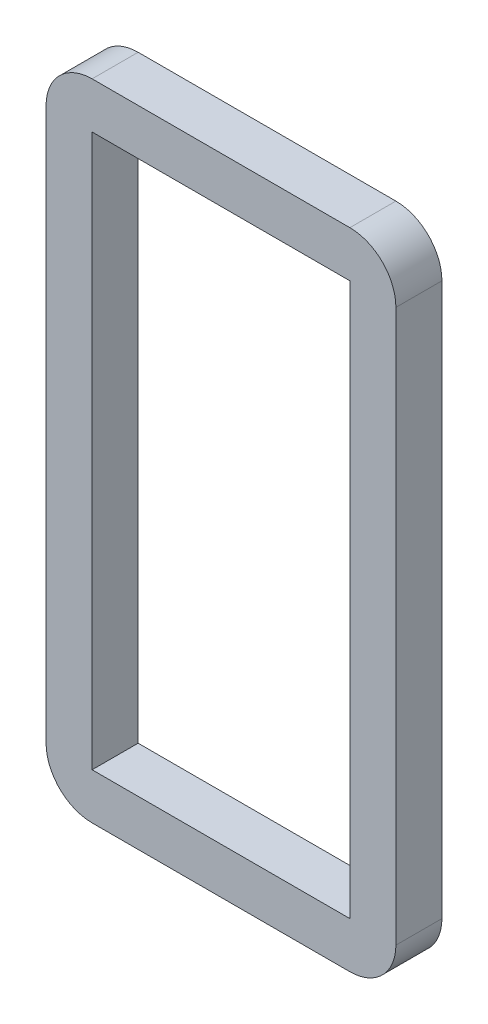
SolidWorks part; units mm, degrees
material "Copper"
ref_plane "Front Plane" through (0, 0, 0) normal (0, 0, 1) x (1, 0, 0)
ref_plane "Top Plane" through (0, 0, 0) normal (0, 1, 0) x (1, 0, 0)
ref_plane "Right Plane" through (0, 0, 0) normal (1, 0, 0) x (0, 0, -1)
sketch "Sketch1" plane through (0, 0, 0) normal (0, 0, 1) x (1, 0, 0)
  line L1 (-14, 30) -> (14, 30)
  line L2 (-14, 30) -> (-14, -30)
  line L3 (-14, -30) -> (14, -30)
  line L4 (14, 30) -> (14, -30)
  line L5 (-14, 30) -> (14, -30) construction
  line L6 (-14, -30) -> (14, 30) construction
  line L7 (-14, 35) -> (14, 35)
  line L8 (-19, 30) -> (-19, -30)
  line L9 (-14, -35) -> (14, -35)
  line L10 (19, 30) -> (19, -30)
  line L11 (-19, 35) -> (19, -35) construction
  line L12 (-19, -35) -> (19, 35) construction
  arc A0 (-19, -30) -> (-14, -35) centre (-14, -30) ccw
  arc A1 (19, -30) -> (14, -35) centre (14, -30) cw
  arc A2 (19, 30) -> (14, 35) centre (14, 30) ccw
  arc A3 (-14, 35) -> (-19, 30) centre (-14, 30) ccw
  point P0 (0, 0)
  point P6 (0, 0)
  dimension "D5" = 5
  dimension "D6" = 5
  dimension "D7" = 5
  dimension "D8" = 5
  dimension "D1" = 60
  dimension "D2" = 28
  dimension "D3" = 70
  dimension "D4" = 38
extrude "Boss-Extrude1" add sketch "Sketch1" along normal mid plane 5
